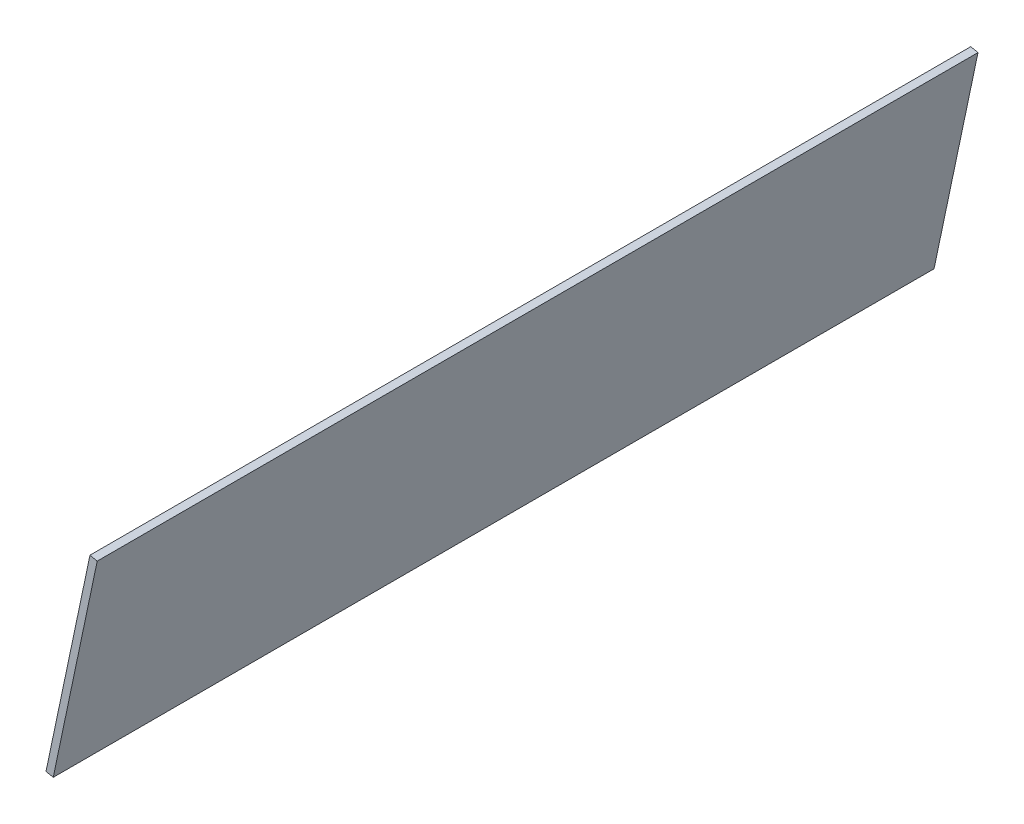
SolidWorks part; units mm, degrees
ref_plane "Front Plane" through (0, 0, 0) normal (0, 0, 1) x (1, 0, 0)
ref_plane "Top Plane" through (0, 0, 0) normal (0, 1, 0) x (1, 0, 0)
ref_plane "Right Plane" through (0, 0, 0) normal (1, 0, 0) x (0, 0, -1)
sketch "Sketch1" plane through (0, 0, 0) normal (0, 0, 1) x (1, 0, 0)
  line L0 (24.224, -184.5309) -> (43.8641, -91.066)
  line L1 (74.6326, -84.2378) -> (-36.1779, -321.8717) construction
  line L2 (24.224, -184.5309) -> (27.4535, -185.2095)
  line L3 (27.4535, -185.2095) -> (47.0936, -91.7446)
  line L4 (47.0936, -91.7446) -> (43.8641, -91.066)
  circle A1 centre (53.023, -69.9683) radius 17.5 construction
  dimension "D1" = 25
  dimension "D2" = 23
  dimension "D3" = 3.3
extrude "Boss-Extrude1" add sketch "Sketch1" along normal up to surface (393.4 mm away)
